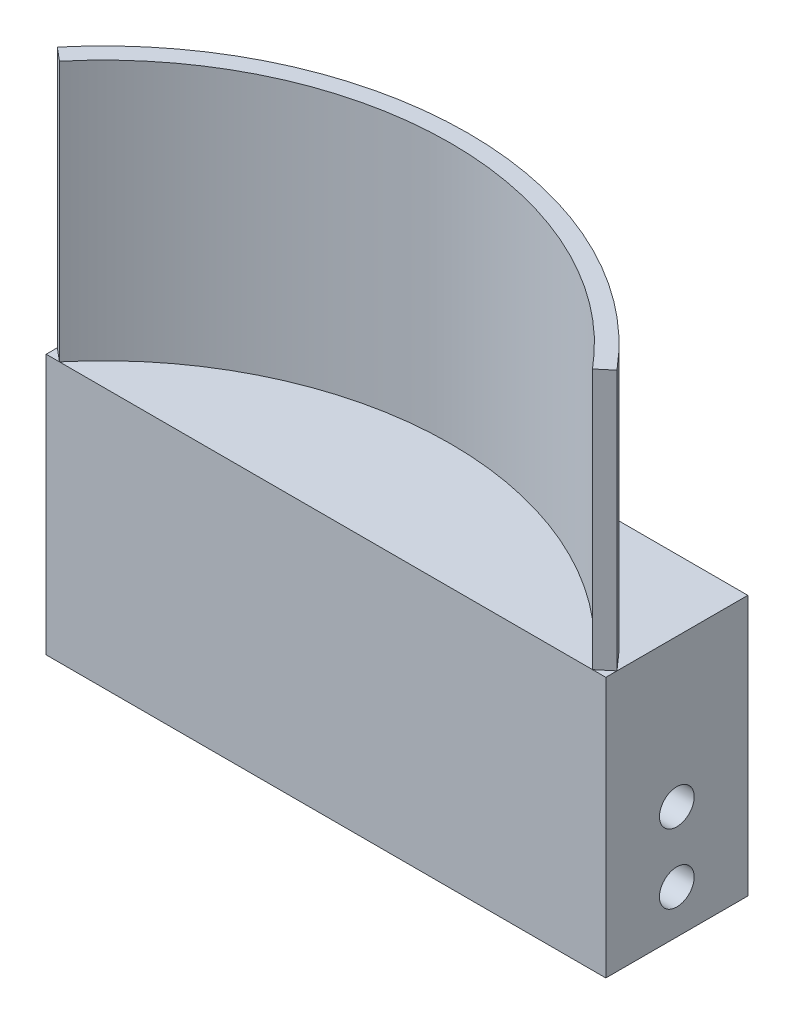
SolidWorks part; units mm, degrees
material "Custom Plastic"
ref_plane "Front Plane" through (0, 0, 0) normal (0, 0, 1) x (1, 0, 0)
ref_plane "Top Plane" through (0, 0, 0) normal (0, 1, 0) x (1, 0, 0)
ref_plane "Right Plane" through (0, 0, 0) normal (1, 0, 0) x (0, 0, -1)
sketch "Sketch2" plane through (0, 0, 0) normal (0, 1, 0) x (1, 0, 0)
  line L0 (-16.1184, 13.4609) -> (-15.3509, 12.8199)
  line L1 (16.1184, 13.4609) -> (15.3509, 12.8199)
  arc A0 (-15.3509, 12.8199) -> (15.3509, 12.8199) centre (0, 0) cw
  arc A1 (-16.1184, 13.4609) -> (16.1184, 13.4609) centre (0, 0) cw
  dimension "D1" = 20
  dimension "D2" = 100.268
  dimension "D3" = 1
extrude "Boss-Extrude1" add sketch "Sketch2" along normal blind 15
sketch "Sketch3" plane through (0, 0, 0) normal (0, -1, 0) x (1, 0, 0)
  line L1 (-16.1184, -12.8199) -> (16.1184, -12.8199)
  line L2 (-16.1184, -12.8199) -> (-16.1184, -21)
  line L3 (-16.1184, -21) -> (16.1184, -21)
  line L4 (16.1184, -12.8199) -> (16.1184, -21)
  arc A0 (-16.1184, -13.4609) -> (16.1184, -13.4609) centre (0, 0) ccw construction
extrude "Boss-Extrude2" add sketch "Sketch3" along normal blind 15
sketch "Sketch4" plane through (16.1184, 0, 0) normal (1, 0, 0) x (0, 0, -1)
  line L0 (21, -15) -> (12.8199, -15) construction
  circle A0 centre (16.91, -12.5) radius 1
  circle A1 centre (16.91, -8.5) radius 1
  point P6 (16.91, -15)
  dimension "D1" = 2
  dimension "D2" = 2
  dimension "D3" = 2.5
  dimension "D4" = 4
extrude "Cut-Extrude1" cut sketch "Sketch4" against normal blind 15
